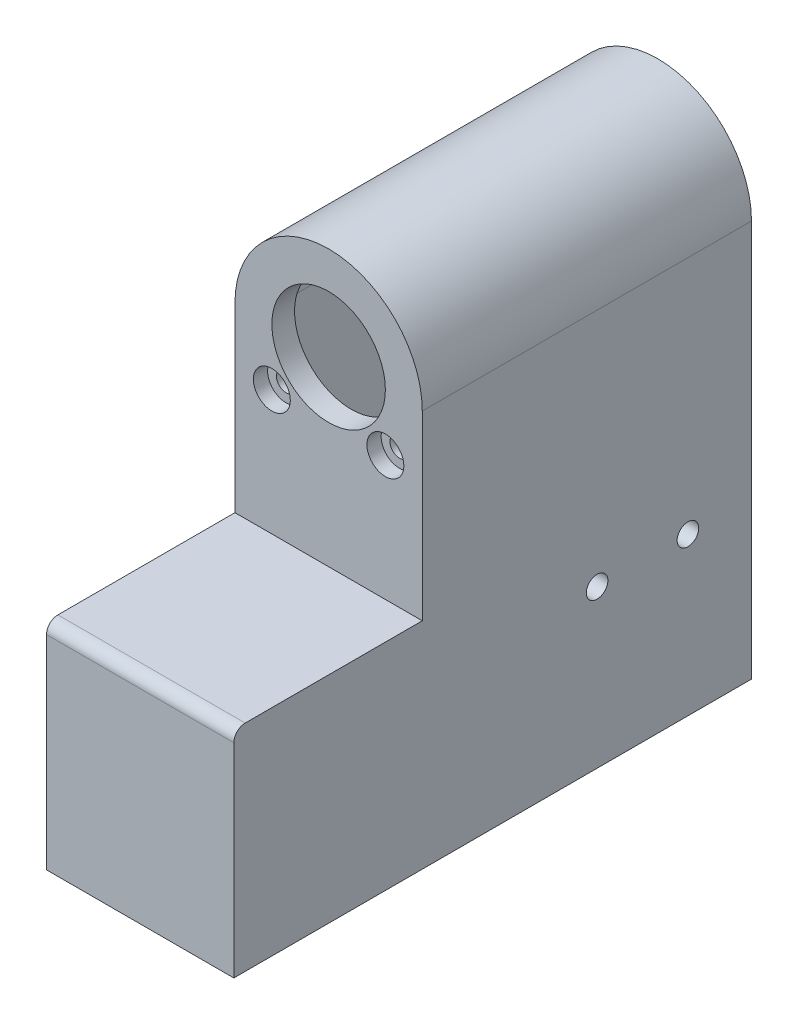
SolidWorks part; units mm, degrees
ref_plane "Front Plane" through (0, 0, 0) normal (0, 0, 1) x (1, 0, 0)
ref_plane "Top Plane" through (0, 0, 0) normal (0, 1, 0) x (1, 0, 0)
ref_plane "Right Plane" through (0, 0, 0) normal (1, 0, 0) x (0, 0, -1)
sketch "Sketch1" plane through (0, 0, 0) normal (0, 0, 1) x (1, 0, 0)
  line L0 (0, 0) -> (33, 0)
  line L1 (16.5, 0) -> (29, 0)
  line L2 (16.5, 0) -> (16.5, 9.4766)
  line L3 (4, 0) -> (4, 80.5)
  line L4 (29, 0) -> (29, 80.5)
  line L5 (0, 0) -> (0, 80.5)
  line L6 (0, 80.5) -> (4, 80.5)
  line L7 (33, 0) -> (33, 80.5)
  line L8 (33, 80.5) -> (29, 80.5)
  arc A0 (33, 80.5) -> (0, 80.5) centre (16.5, 80.5) ccw
  arc A1 (4, 80.5) -> (29, 80.5) centre (16.5, 80.5) cw
  point P5 (4, 0)
  dimension "D1" = 33
  dimension "D2" = 12.5
  dimension "D3" = 80.5
extrude "Boss-Extrude1" add sketch "Sketch1" along normal blind 71 contours L6 L5 L0 L3 | L6 A1 L8 A0 | L7 L8 L4 L0
sketch "Sketch2" plane through (0, 0, 71) normal (0, 0, 1) x (1, 0, 0)
  line L2 (33, 48.5) -> (0, 48.5)
  line L3 (0, 0) -> (0, 80.5) construction
  line L4 (0, 48.5) -> (0, 80.5)
  line L5 (33, 0) -> (33, 80.5) construction
  line L6 (33, 48.5) -> (33, 80.5)
  arc A0 (33, 80.5) -> (0, 80.5) centre (16.5, 80.5) ccw construction
  arc A1 (33, 80.5) -> (0, 80.5) centre (16.5, 80.5) ccw
  point P8 (16.5, 48.5)
extrude "Boss-Extrude2" add sketch "Sketch2" against normal blind 4
sketch "Sketch3" plane through (0, 0, 67) normal (0, 0, -1) x (-1, 0, 0)
  line L0 (-4, 48.5) -> (-29, 48.5) construction
  line L1 (-4, 48.5) -> (-29, 48.5)
  line L3 (-29, 44.5) -> (-4, 44.5)
  line L5 (0, 0) -> (0, 80.5) construction
  line L6 (0, 0) -> (0, 48.5)
  line L7 (-4, 48.5) -> (0, 48.5)
  line L8 (0, 0) -> (-3.8379, 0)
  line L9 (-4, 44.5) -> (-3.8379, 0)
  line L10 (-16.5, 44.5) -> (-16.5, 41.0104)
  line L11 (-33, 0) -> (-33, 48.5)
  line L12 (-29, 48.5) -> (-33, 48.5)
  line L13 (-29, 44.5) -> (-29.1621, 0)
  line L14 (-33, 0) -> (-29.1621, 0)
  line M8 (-29, 48.5) -> (-4, 48.5)
extrude "Boss-Extrude3" add sketch "Sketch3" against normal blind 34.2 contours L11 L14 L13 L3 L9 L8 L6 L7 L12 M8
sketch "Sketch4" plane through (0, 0, 0) normal (0, 0, -1) x (-1, 0, 0)
  line L6 (-4, 80.5) -> (-4, 0)
  line L7 (-4, 0) -> (0, 0)
  line L8 (0, 0) -> (0, 80.5)
  line L9 (-33, 80.5) -> (-33, 0)
  line L10 (-33, 0) -> (-29, 0)
  line L11 (-29, 0) -> (-29, 80.5)
  line L12 (-4, 80.5) -> (-4, 0)
  line L13 (-4, 0) -> (0, 0)
  line L14 (0, 0) -> (0, 80.5)
  line L15 (-33, 80.5) -> (-33, 0)
  line L16 (-33, 0) -> (-29, 0)
  line L17 (-29, 0) -> (-29, 80.5)
  arc A2 (0, 80.5) -> (-33, 80.5) centre (-16.5, 80.5) ccw
  arc A3 (-4, 80.5) -> (-29, 80.5) centre (-16.5, 80.5) ccw
  arc A4 (0, 80.5) -> (-33, 80.5) centre (-16.5, 80.5) ccw
  arc A5 (-4, 80.5) -> (-29, 80.5) centre (-16.5, 80.5) ccw
  dimension "D1" = 0
extrude "Cut-Extrude1" cut sketch "Sketch4" against normal blind 13
sketch "Sketch5" plane through (0, 0, 71) normal (0, 0, 1) x (1, 0, 0)
  line L0 (0, 80.5) -> (33, 80.5)
  circle A0 centre (16.5, 80.5) radius 10
  dimension "D1" = 20
extrude "Cut-Extrude2" cut sketch "Sketch5" against normal blind 13 contours L0 A0 | L0 A0
sketch "Sketch6" plane through (0, 0, 71) normal (0, 0, 1) x (1, 0, 0)
  line L0 (16.5, 70.5) -> (16.5, 73.1374)
  line L1 (16.5, 70.5) -> (33, 70.5)
  line L2 (33, 48.5) -> (33, 80.5) construction
  circle A0 centre (26.5, 70.5) radius 1.7
  circle A1 centre (6.5, 70.5) radius 1.7
  dimension "D2" = 3.4
  dimension "D1" = 6.5
extrude "Cut-Extrude3" cut sketch "Sketch6" against normal blind 13 contours A1 | L1 A0 | L1 A0
sketch "Sketch7" plane through (0, 0, 71) normal (0, 0, 1) x (1, 0, 0)
  circle A0 centre (6.5, 70.5) radius 3.25
  circle A1 centre (26.5, 70.5) radius 3.25
  dimension "D1" = 6.5
extrude "Cut-Extrude4" cut sketch "Sketch7" against normal blind 2.5
sketch "Sketch9" plane through (0, 0, 0) normal (0, -1, 0) x (1, 0, 0)
  line L0 (29.1621, 101.2) -> (29.1621, 71) construction
  line L1 (29.1621, 101.2) -> (29.1621, 71)
  line L2 (29.1621, 71) -> (29, 71)
  line L3 (29, 71) -> (29, 120)
  line L4 (29, 120) -> (29.1621, 101.2)
  line L6 (29, 67) -> (4, 67) construction
  line L7 (29, 67) -> (4, 67)
  line L8 (16.5, 67) -> (16.5, 71)
  line L9 (4, 120) -> (3.8379, 101.2)
  line L10 (4, 71) -> (4, 120)
  line L11 (3.8379, 71) -> (4, 71)
  line L12 (3.8379, 101.2) -> (3.8379, 71)
extrude "Boss-Extrude4" add sketch "Sketch9" against normal up to surface (44.5 mm away) contours L4 L1 L2 L3 | L9 L12 L11 L10 up to face at (16.5, 44.5, 79.7333)
sketch "Sketch10" plane through (0, 0, 101.2) normal (0, 0, 1) x (1, 0, 0)
  line L1 (40.2439, -6.5645) -> (-5.7585, -6.5645)
  line L2 (40.2439, -6.5645) -> (40.2439, 55.1467)
  line L3 (40.2439, 55.1467) -> (-5.7585, 55.1467)
  line L4 (-5.7585, -6.5645) -> (-5.7585, 55.1467)
  line L5 (40.2439, -6.5645) -> (-5.7585, 55.1467) construction
  line L6 (40.2439, 55.1467) -> (-5.7585, -6.5645) construction
  point P0 (17.2427, 24.2911)
extrude "Cut-Extrude5" cut sketch "Sketch10" along normal blind 42
sketch "Sketch11" plane through (0, 0, 101.2) normal (0, 0, 1) x (1, 0, 0)
  line L0 (29, 0) -> (4, 0)
  line L8 (4, 44.5) -> (29, 44.5)
  line L9 (29, 44.5) -> (29, 0)
  line L10 (29, 0) -> (33, 0)
  line L11 (33, 0) -> (33, 48.5)
  line L12 (33, 48.5) -> (0, 48.5)
  line L13 (0, 48.5) -> (0, 0)
  line L14 (0, 0) -> (4, 0)
  line L15 (4, 0) -> (4, 44.5)
  line L18 (29, 0) -> (33, 0)
  line L19 (33, 0) -> (33, 48.5)
  line L20 (33, 48.5) -> (0, 48.5)
  line L21 (0, 48.5) -> (0, 0)
  line L22 (0, 0) -> (4, 0)
  dimension "D1" = 0
extrude "Boss-Extrude5" add sketch "Sketch11" along normal blind 4
sketch "Sketch12" plane through (0, 0, 0) normal (0, -1, 0) x (1, 0, 0)
  line L8 (4, 13) -> (4, 101.2)
  line L9 (4, 101.2) -> (29, 101.2)
  line L10 (29, 101.2) -> (29, 13)
  line L11 (29, 13) -> (33, 13)
  line L12 (33, 13) -> (33, 105.2)
  line L13 (33, 105.2) -> (0, 105.2)
  line L14 (0, 105.2) -> (0, 13)
  line L15 (0, 13) -> (4, 13)
  line L16 (4, 13) -> (4, 101.2)
  line L17 (4, 101.2) -> (29, 101.2)
  line L18 (29, 101.2) -> (29, 13)
  line L19 (29, 13) -> (33, 13)
  line L20 (33, 13) -> (33, 105.2)
  line L21 (33, 105.2) -> (0, 105.2)
  line L22 (0, 105.2) -> (0, 13)
  line L23 (0, 13) -> (4, 13)
  dimension "D1" = 0
extrude "Cut-Extrude6" cut sketch "Sketch12" against normal blind 10.6
sketch "Sketch13" plane through (0, 0, 0) normal (-1, 0, 0) x (0, 0, 1)
  line L0 (105.2, 10.6) -> (13, 10.6) construction
  line L1 (13, 10.6) -> (13, 80.5) construction
  circle A0 centre (40.2, 38.3) radius 1.9
  circle A1 centre (24.2, 38.3) radius 1.9
  dimension "D1" = 27.7
  dimension "D2" = 3.8
  dimension "D3" = 27.2
  dimension "D4" = 16
extrude "Cut-Extrude7" cut sketch "Sketch13" against normal up to surface (33 mm away) contours A1 | A0 up to face at (33, 46.5333, 63.0667)
sketch "Sketch14" plane through (0, 0, 101.2) normal (0, 0, -1) x (-1, 0, 0)
  line L4 (-29, 10.6) -> (-4, 10.6)
  line L5 (-4, 10.6) -> (-4, 44.5)
  line L6 (-4, 44.5) -> (-29, 44.5)
  line L7 (-29, 44.5) -> (-29, 10.6)
  line L8 (-29, 10.6) -> (-4, 10.6)
  line L9 (-4, 10.6) -> (-4, 44.5)
  line L10 (-4, 44.5) -> (-29, 44.5)
  line L11 (-29, 44.5) -> (-29, 10.6)
  dimension "D1" = 0
extrude "Boss-Extrude6" add sketch "Sketch14" along normal blind 1
sketch "Sketch15" plane through (0, 10.6, 0) normal (0, -1, 0) x (1, 0, 0)
  line L0 (29, 100.2) -> (4, 100.2) construction
  line L1 (29, 100.2) -> (4, 100.2)
  line L2 (16.5, 100.2) -> (16.5, 101.5)
  line L3 (16.5, 105.2) -> (16.5, 103.9)
  line L4 (33, 105.2) -> (0, 105.2) construction
  line L5 (16.5, 101.5) -> (6.3, 101.5)
  line L6 (16.5, 101.5) -> (26.7, 101.5)
  line L7 (26.7, 101.5) -> (26.7, 103.9)
  line L8 (26.7, 103.9) -> (6.3, 103.9)
  line L9 (6.3, 103.9) -> (6.3, 101.5)
  dimension "D1" = 1.3
  dimension "D2" = 1.3
  dimension "D3" = 10.2
  dimension "D4" = 10.2
extrude "Cut-Extrude8" cut sketch "Sketch15" against normal blind 15 contours L8 L9 L5 L6 L7
sketch "Sketch16" plane through (0, 10.6, 0) normal (0, -1, 0) x (1, 0, 0)
  line L1 (26.7, 103.9) -> (6.3, 103.9) construction
  line L3 (21.7, 103.9) -> (21.7, 105.2)
  line L4 (33, 105.2) -> (0, 105.2) construction
  line L5 (21.7, 105.2) -> (11.3, 105.2)
  line L6 (11.3, 105.2) -> (11.3, 103.9)
  line L7 (21.7, 103.9) -> (11.3, 103.9)
  point P0 (16.5, 103.9)
  point P2 (16.5, 105.2)
  dimension "D1" = 10.4
extrude "Cut-Extrude9" cut sketch "Sketch16" against normal up to surface (15 mm away) up to face at (16.5, 25.6, 102.7)
sketch "Sketch17" plane through (0, 25.6, 0) normal (0, -1, 0) x (1, 0, 0)
  line L8 (26.7, 103.9) -> (21.7, 103.9)
  line L9 (21.7, 103.9) -> (21.7, 105.2)
  line L10 (21.7, 105.2) -> (11.3, 105.2)
  line L11 (11.3, 105.2) -> (11.3, 103.9)
  line L12 (11.3, 103.9) -> (6.3, 103.9)
  line L13 (6.3, 103.9) -> (6.3, 101.5)
  line L14 (6.3, 101.5) -> (26.7, 101.5)
  line L15 (26.7, 101.5) -> (26.7, 103.9)
  line L16 (26.7, 103.9) -> (21.7, 103.9)
  line L17 (21.7, 103.9) -> (21.7, 105.2)
  line L18 (21.7, 105.2) -> (11.3, 105.2)
  line L19 (11.3, 105.2) -> (11.3, 103.9)
  line L20 (11.3, 103.9) -> (6.3, 103.9)
  line L21 (6.3, 103.9) -> (6.3, 101.5)
  line L22 (6.3, 101.5) -> (26.7, 101.5)
  line L23 (26.7, 101.5) -> (26.7, 103.9)
  dimension "D1" = 0
extrude "Boss-Extrude7" add sketch "Sketch17" along normal up to surface (15 mm away) up to face at (16.5, 10.6, 80.7375)
sketch "Sketch19" plane through (0, 0, 105.2) normal (0, 0, 1) x (1, 0, 0)
  line L4 (0, 48.5) -> (0, 10.6)
  line L5 (0, 10.6) -> (33, 10.6)
  line L6 (33, 10.6) -> (33, 48.5)
  line L7 (33, 48.5) -> (0, 48.5)
  line L8 (0, 48.5) -> (0, 10.6)
  line L9 (0, 10.6) -> (33, 10.6)
  line L10 (33, 10.6) -> (33, 48.5)
  line L11 (33, 48.5) -> (0, 48.5)
  dimension "D1" = 0
extrude "Cut-Extrude10" cut sketch "Sketch19" against normal blind 1
fillet "Fillet1" radius 2 1 edges at (16.5, 48.5, 104.2)
